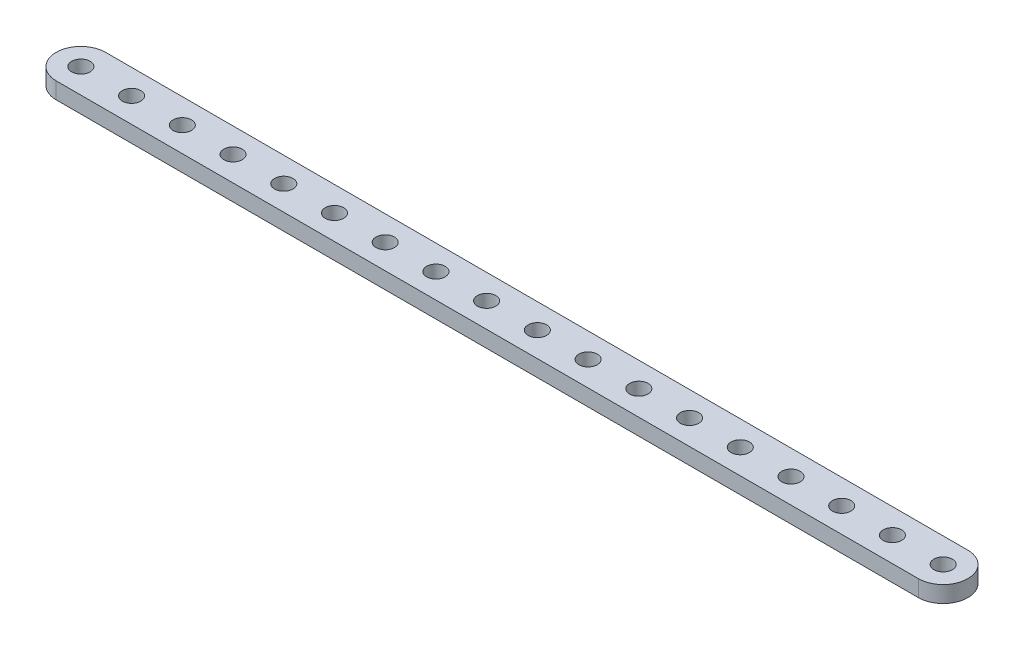
SolidWorks part; units mm, degrees
ref_plane "Front Plane" through (0, 0, 0) normal (0, 0, 1) x (1, 0, 0)
ref_plane "Top Plane" through (0, 0, 0) normal (0, 1, 0) x (1, 0, 0)
ref_plane "Right Plane" through (0, 0, 0) normal (1, 0, 0) x (0, 0, -1)
ref_plane "Plane1" through (0, 6.35, 0) normal (0, 1, 0) x (1, 0, 0)
sketch "Sketch1" plane through (0, 6.35, 0) normal (0, 1, 0) x (1, 0, 0)
  line L0 (97.79, 4.7625) -> (-97.79, 4.7625)
  line L1 (-97.79, -4.7625) -> (97.79, -4.7625)
  arc A0 (97.79, -4.7625) -> (97.79, 4.7625) centre (97.79, 0) ccw
  arc A1 (-97.79, 4.7625) -> (-97.79, -4.7625) centre (-97.79, 0) ccw
  circle A2 centre (97.79, 0) radius 1.778
  circle A3 centre (88.011, 0) radius 1.778
  circle A4 centre (78.232, 0) radius 1.778
  circle A5 centre (68.453, 0) radius 1.778
  circle A6 centre (58.674, 0) radius 1.778
  circle A7 centre (48.895, 0) radius 1.778
  circle A8 centre (39.116, 0) radius 1.778
  circle A9 centre (29.337, 0) radius 1.778
  circle A10 centre (19.558, 0) radius 1.778
  circle A11 centre (9.779, 0) radius 1.778
  circle A12 centre (0, 0) radius 1.778
  circle A13 centre (-9.779, 0) radius 1.778
  circle A14 centre (-19.558, 0) radius 1.778
  circle A15 centre (-29.337, 0) radius 1.778
  circle A16 centre (-39.116, 0) radius 1.778
  circle A17 centre (-48.895, 0) radius 1.778
  circle A18 centre (-58.674, 0) radius 1.778
  circle A19 centre (-68.453, 0) radius 1.778
  circle A20 centre (-78.232, 0) radius 1.778
  circle A21 centre (-88.011, 0) radius 1.778
  circle A22 centre (-97.79, 0) radius 1.778
extrude "Boss-Extrude1" add sketch "Sketch1" against normal blind 6.35
sketch "Sketch2" plane through (0, 6.35, 0) normal (0, 1, 0) x (1, 0, 0)
  line L0 (-97.79, -4.7625) -> (97.79, -4.7625) construction
  line L1 (97.79, 4.7625) -> (-97.79, 4.7625) construction
  line L2 (-68.453, -4.7625) -> (-109.3873, -4.7625)
  line L3 (-109.3873, -4.7625) -> (-109.3873, 4.7625)
  line L4 (-109.3873, 4.7625) -> (-68.453, 4.7625)
  arc A0 (-68.453, -4.7625) -> (-68.453, 4.7625) centre (-68.453, 0) cw
extrude "Cut-Extrude1" cut sketch "Sketch2" against normal through all both and the other way through all
sketch "Sketch3" plane through (0, 6.35, 0) normal (0, 1, 0) x (1, 0, 0)
  line L1 (-128.1733, -49.476) -> (115.6725, -49.476)
  line L2 (-128.1733, -49.476) -> (-128.1733, 45.0585)
  line L3 (-128.1733, 45.0585) -> (115.6725, 45.0585)
  line L4 (115.6725, -49.476) -> (115.6725, 45.0585)
extrude "Cut-Extrude2" cut sketch "Sketch3" against normal blind 3.175
sketch "Sketch4" plane through (0, 3.175, 0) normal (0, 1, 0) x (1, 0, 0)
  line L0 (-73.2155, 0) -> (102.5525, 0) construction
  arc A0 (-68.453, 4.7625) -> (-68.453, -4.7625) centre (-68.453, 0) ccw construction
  arc A1 (97.79, -4.7625) -> (97.79, 4.7625) centre (97.79, 0) ccw construction
